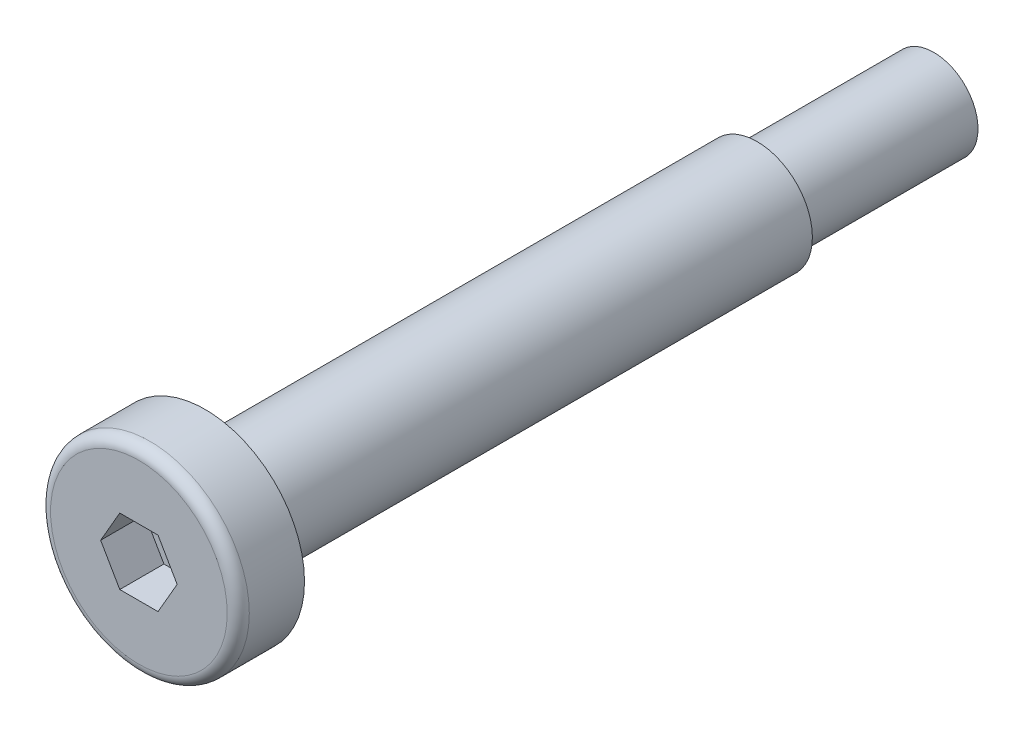
SolidWorks part; units mm, degrees
ref_plane "前视基准面" through (0, 0, 0) normal (0, 0, 1) x (1, 0, 0)
ref_plane "上视基准面" through (0, 0, 0) normal (0, 1, 0) x (1, 0, 0)
ref_plane "右视基准面" through (0, 0, 0) normal (1, 0, 0) x (0, 0, -1)
other "Configuration Table"
sketch "草图1" plane through (0, 0, 0) normal (0, 0, 1) x (1, 0, 0)
  circle A0 centre (0, 0) radius 4.5
  dimension "D1" = 9
extrude "凸台-拉伸1" add sketch "草图1" along normal blind 3
sketch "草图2" plane through (0, 0, 0) normal (0, 0, 1) x (1, 0, 0)
  circle A0 centre (0, 0) radius 2.5
  dimension "D1" = 5
extrude "凸台-拉伸2" add sketch "草图2" against normal blind 25
sketch "草图3" plane through (0, 0, 0) normal (0, 0, 1) x (1, 0, 0)
  circle A0 centre (0, 0) radius 2
  dimension "D1" = 4
extrude "凸台-拉伸3" add sketch "草图3" against normal blind 8 from surface at -25 starting at face at (2.5, 0, -25)
sketch "草图4" plane through (0, 0, 0) normal (0, 0, 1) x (1, 0, 0)
  line L1 (1.7321, 0) -> (0.866, 1.5)
  line L2 (0.866, 1.5) -> (-0.866, 1.5)
  line L3 (-0.866, 1.5) -> (-1.7321, 0)
  line L4 (-1.7321, 0) -> (-0.866, -1.5)
  line L5 (-0.866, -1.5) -> (0.866, -1.5)
  line L6 (0.866, -1.5) -> (1.7321, 0)
  circle A0 centre (0, 0) radius 1.5 construction
  dimension "D1" = 3
extrude "切除-拉伸1" cut sketch "草图4" against normal blind 2 from surface at 3 starting at face at (4.5, 0, 3)
fillet "圆角1" radius 0.5 1 edges at (4.5, 0, 3)
